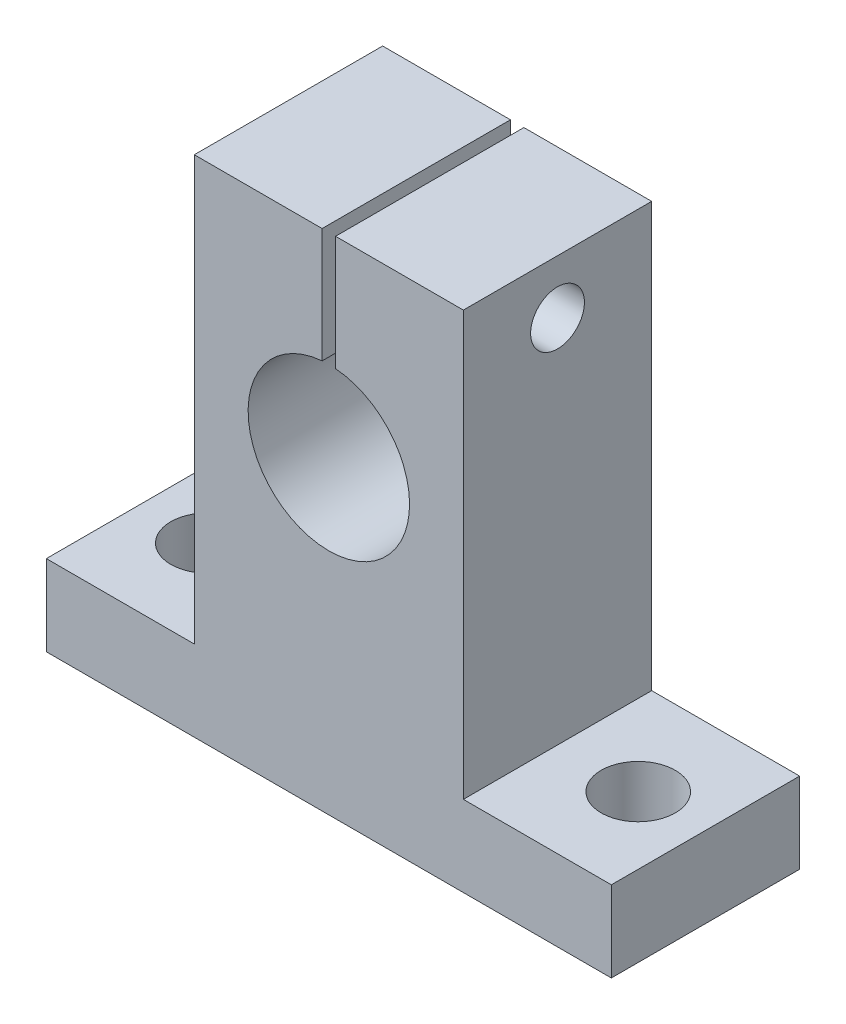
SolidWorks part; units mm, degrees
ref_plane "Front" through (0, 0, 0) normal (0, 0, 1) x (1, 0, 0)
ref_plane "Top" through (0, 0, 0) normal (0, 1, 0) x (1, 0, 0)
ref_plane "Right" through (0, 0, 0) normal (1, 0, 0) x (0, 0, -1)
sketch "Sketch1" plane through (0, 0, 0) normal (0, 0, 1) x (1, 0, 0)
  line L0 (0, 37.5) -> (0, -11.1975) construction
  line L1 (-21, 0) -> (21, 0)
  line L2 (-21, 0) -> (-21, 6)
  line L3 (-21, 6) -> (-10, 6)
  line L4 (21, 0) -> (21, 6)
  line L5 (10, 6) -> (21, 6)
  line L7 (-10, 6) -> (-10, 37.5)
  line L8 (-10, 37.5) -> (10, 37.5)
  line L9 (10, 6) -> (10, 37.5)
  circle A0 centre (0, 23) radius 6
  dimension "D4" = 12
  dimension "D1" = 6
  dimension "D2" = 42
  dimension "D3" = 20
  dimension "D5" = 37.5
  dimension "20" = 23
extrude "Boss-Extrude1" add sketch "Sketch1" along normal blind 14
sketch "Sketch2" plane through (10, 0, 0) normal (1, 0, 0) x (0, 0, -1)
  line L0 (-14, 37.5) -> (0, 37.5) construction
  line L1 (-7, 37.5) -> (-7, 14.0812) construction
  circle A0 centre (-7, 33.5) radius 2
  dimension "D1" = 4
  dimension "D2" = 4
sketch "Sketch3" plane through (0, 0, 14) normal (0, 0, 1) x (1, 0, 0)
  line L0 (10, 37.5) -> (-10, 37.5) construction
  line L1 (-0.5, 37.5) -> (0.5, 37.5)
  line L2 (-0.5, 37.5) -> (-0.5, 21.0098)
  line L3 (-0.5, 21.0098) -> (0.5, 21.0098)
  line L4 (0.5, 37.5) -> (0.5, 21.0098)
  line L5 (0, 37.5) -> (0, 12.111) construction
  dimension "D1" = 1
extrude "Cut-Extrude1" cut sketch "Sketch3" against normal blind 19 contours L4 L3 L2 L1
extrude "Cut-Extrude3" cut sketch "Sketch2" against normal blind 31 contours A0
sketch "Sketch5" plane through (0, 6, 0) normal (0, 1, 0) x (1, 0, 0)
  line L0 (0, 7.6779) -> (0, -23.3122) construction
  line L1 (21, -7) -> (-21, -7) construction
  line L4 (21, -14) -> (21, 0) construction
  line L5 (-21, -14) -> (-21, 0) construction
  circle A0 centre (16, -7) radius 2.75
  circle A1 centre (-16, -7) radius 2.75
  dimension "D1" = 32
  dimension "D2" = 5.5
extrude "Cut-Extrude5" cut sketch "Sketch5" against normal blind 22
